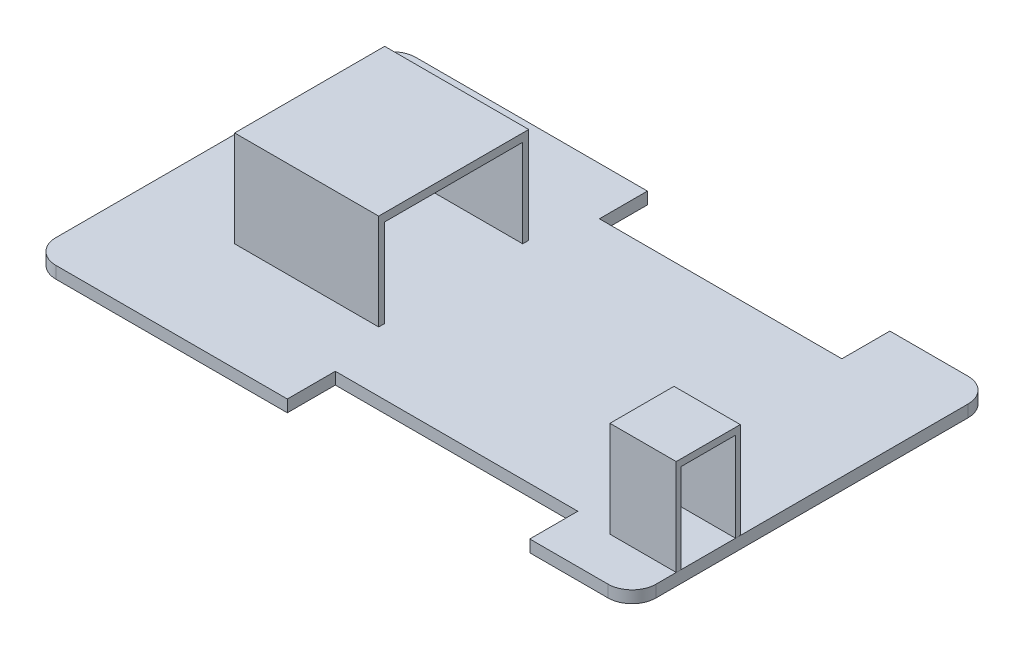
SolidWorks part; units mm, degrees
ref_plane "Front Plane" through (0, 0, 0) normal (0, 0, 1) x (1, 0, 0)
ref_plane "Top Plane" through (0, 0, 0) normal (0, 1, 0) x (1, 0, 0)
ref_plane "Right Plane" through (0, 0, 0) normal (1, 0, 0) x (0, 0, -1)
sketch "Sketch1" plane through (0, 0, 0) normal (0, 1, 0) x (1, 0, 0)
  line L0 (106.4075, 20) -> (207.4075, 20)
  line L1 (0, 0) -> (106.4075, 0)
  line L2 (0, 0) -> (0, 150)
  line L3 (0, 150) -> (106.4075, 150)
  line L4 (250, 0) -> (250, 150)
  line L6 (106.4075, 150) -> (106.4075, 130)
  line L7 (106.4075, 130) -> (207.4075, 130)
  line L8 (207.4075, 150) -> (207.4075, 130)
  line L9 (106.4075, 20) -> (106.4075, 0)
  line L11 (207.4075, 20) -> (207.4075, 0)
  line L12 (207.4075, 150) -> (250, 150)
  line L13 (207.4075, 0) -> (250, 0)
  dimension "D1" = 250
  dimension "D2" = 150
  dimension "D3" = 101
  dimension "D4" = 20
extrude "Boss-Extrude1" add sketch "Sketch1" along normal blind 5
sketch "Sketch2" plane through (0, 5, 0) normal (0, 1, 0) x (1, 0, 0)
  line L0 (249.982, 45.107) -> (222.3811, 45.107)
  line L1 (249.982, 20.4156) -> (222.3811, 20.4156)
  line L2 (249.982, 20.4156) -> (249.982, 18.4156)
  line L3 (249.982, 18.4156) -> (222.3811, 18.4156)
  line L4 (222.3811, 20.4156) -> (222.3811, 18.4156)
  line L5 (249.982, 45.107) -> (249.982, 43.107)
  line L6 (249.982, 43.107) -> (222.3811, 43.107)
  line L7 (222.3811, 45.107) -> (222.3811, 43.107)
  line L8 (99.461, 105) -> (39.461, 105)
  line L9 (99.461, 47.5) -> (39.461, 47.5)
  line L10 (99.461, 47.5) -> (99.461, 45)
  line L11 (99.461, 45) -> (39.461, 45)
  line L12 (39.461, 47.5) -> (39.461, 45)
  line L13 (99.461, 105) -> (99.461, 107.5)
  line L14 (99.461, 107.5) -> (39.461, 107.5)
  line L15 (39.461, 105) -> (39.461, 107.5)
  line L16 (106.4075, 150) -> (0, 150) construction
  dimension "D1" = 60
  dimension "D2" = 2.5
  dimension "D3" = 60
  dimension "D4" = 42.5
  dimension "D5" = 2
extrude "Boss-Extrude2" add sketch "Sketch2" along normal blind 40
sketch "Sketch4" plane through (0, 0, -43.107) normal (0, 0, 1) x (1, 0, 0)
  line L0 (249.982, 45) -> (249.982, 5) construction
  line L1 (222.3811, 45) -> (249.982, 45)
  line L2 (222.3811, 45) -> (222.3811, 42.1659)
  line L3 (222.3811, 42.1659) -> (249.982, 42.1659)
  line L4 (249.982, 45) -> (249.982, 42.1659)
extrude "Boss-Extrude4" add sketch "Sketch4" along normal up to surface (22.6913 mm away) contours L3 L4 L1 L2 up to face at (236.1815, 25, -20.4156)
sketch "Sketch5" plane through (0, 0, -47.5) normal (0, 0, -1) x (-1, 0, 0)
  line L0 (-39.461, 45) -> (-39.461, 5) construction
  line L1 (-99.461, 45) -> (-39.461, 45)
  line L2 (-99.461, 45) -> (-99.461, 41.6404)
  line L3 (-99.461, 41.6404) -> (-39.461, 41.6404)
  line L4 (-39.461, 45) -> (-39.461, 41.6404)
extrude "Boss-Extrude5" add sketch "Sketch5" along normal up to surface (57.5 mm away) contours L3 L4 L1 L2 up to face at (69.461, 25, -105)
fillet "Fillet1" radius 10 4 edges at (250, 2.5, 0) (250, 2.5, -150) (0, 2.5, -150) (0, 2.5, 0)
